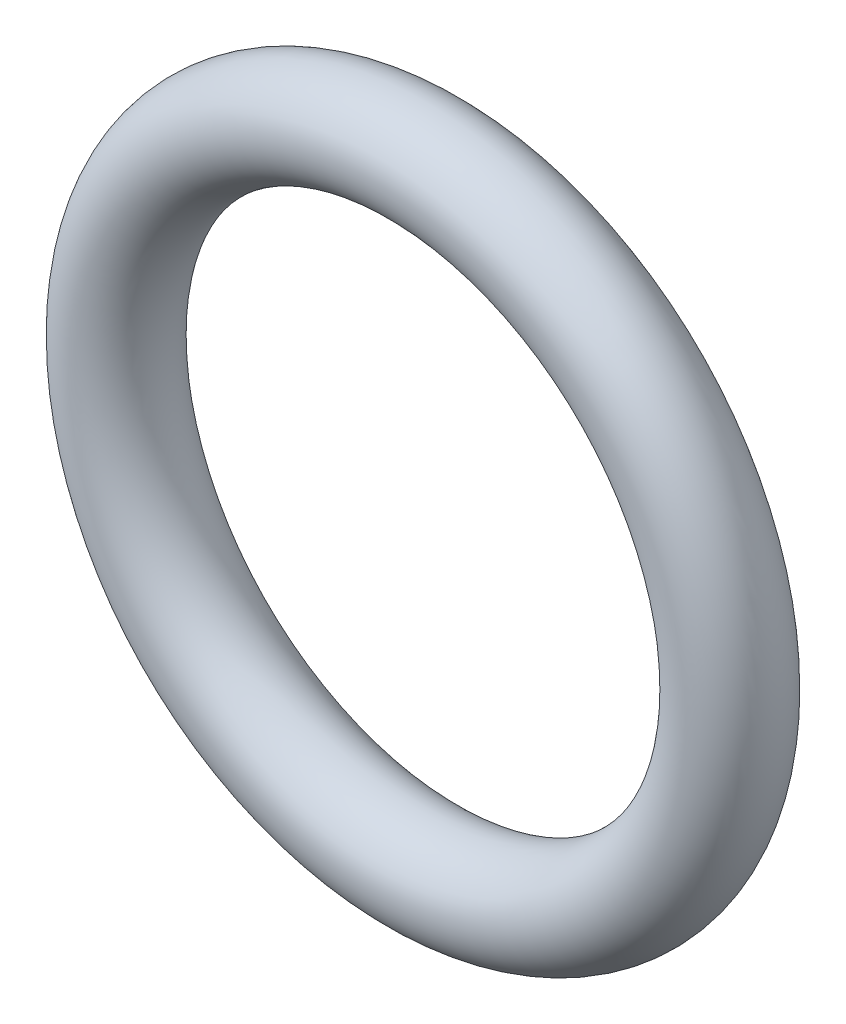
SolidWorks part; units mm, degrees
ref_plane "Front" through (0, 0, 0) normal (0, 0, 1) x (1, 0, 0)
ref_plane "Top" through (0, 0, 0) normal (0, 1, 0) x (1, 0, 0)
ref_plane "Right" through (0, 0, 0) normal (1, 0, 0) x (0, 0, -1)
sketch "Sketch1" plane through (0, 0, 0) normal (1, 0, 0) x (0, -1, 0)
  line L0 (0, -0.889) -> (0, 0.889) construction
  line L2 (-7.0409, 0) -> (7.0409, 0) construction
  line L3 (-4.6228, 0) -> (4.6228, 0) construction
  circle A0 centre (5.5118, 0) radius 0.889
  point P9 (4.6228, 0)
  point P10 (6.4008, 0)
  point P13 (5.5118, 0.889)
  point P14 (5.5118, -0.889)
  dimension "Width" = 1.778
  dimension "ID" = 9.2456
revolve "Revolve1" add sketch "Sketch1" angle 360 about L0
